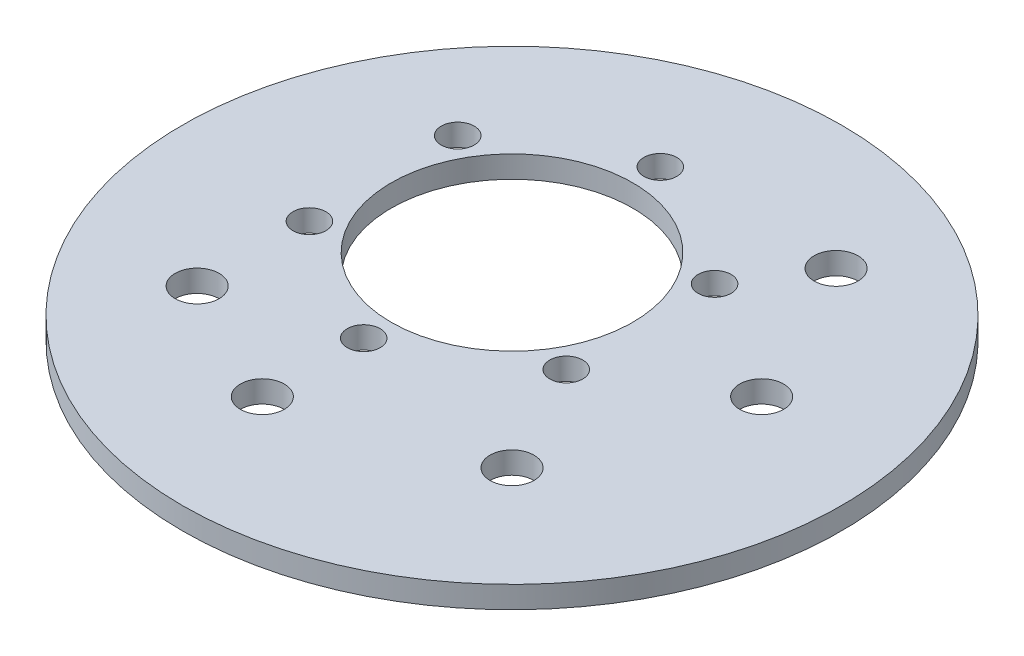
SolidWorks part; units mm, degrees
ref_plane "前视基准面" through (0, 0, 0) normal (0, 0, 1) x (1, 0, 0)
ref_plane "上视基准面" through (0, 0, 0) normal (0, 1, 0) x (1, 0, 0)
ref_plane "右视基准面" through (0, 0, 0) normal (1, 0, 0) x (0, 0, -1)
sketch "Sketch1" plane through (0, 0, 0) normal (0, 1, 0) x (1, 0, 0)
  circle A0 centre (0, 0) radius 30
extrude "Boss-Extrude1" add sketch "Sketch1" along normal blind 2
sketch "Sketch4" plane through (0, 2, 0) normal (0, 1, 0) x (1, 0, 0)
  line L0 (-4.9497, -11.0503) -> (-4.9497, -24.5051) construction
  line L1 (17.6777, -17.6777) -> (6.364, -6.364) construction
  line L2 (4.5962, -4.5962) -> (-21.2132, 21.2132) construction
  line L3 (11.0503, 4.9497) -> (24.5051, 4.9497) construction
  circle A0 centre (0, 0) radius 30 construction
  circle A1 centre (-4.9497, 4.9497) radius 16 construction
  circle A2 centre (0, 0) radius 25 construction
  circle A3 centre (-4.9497, 4.9497) radius 11
  circle A4 centre (-4.9497, 4.9497) radius 13.5 construction
  circle A5 centre (-4.9497, 18.4497) radius 1.5
  circle A6 centre (6.7416, 11.6997) radius 1.5
  circle A7 centre (6.7416, -1.8003) radius 1.5
  circle A8 centre (-4.9497, -8.5503) radius 1.5
  circle A9 centre (-16.6411, -1.8003) radius 1.5
  circle A10 centre (-16.6411, 11.6997) radius 1.5
  arc A12 (17.7777, 4.9497) -> (-4.9497, -17.7777) centre (-2.2983, 2.2983) cw
  circle A13 centre (17.7777, 4.9497) radius 2
  circle A14 centre (12.0208, -12.0208) radius 2
  circle A15 centre (-4.9497, -17.7777) radius 2
  circle A16 centre (11.0503, 18.4497) radius 2
  circle A17 centre (-16.6411, -12.0208) radius 2
  point P0 (12.0208, -12.0208)
  point P33 (12.0208, -12.0208)
  dimension "D1" = 23
  dimension "D2" = 6
extrude "Cut-Extrude3" cut sketch "Sketch4" against normal up to next
